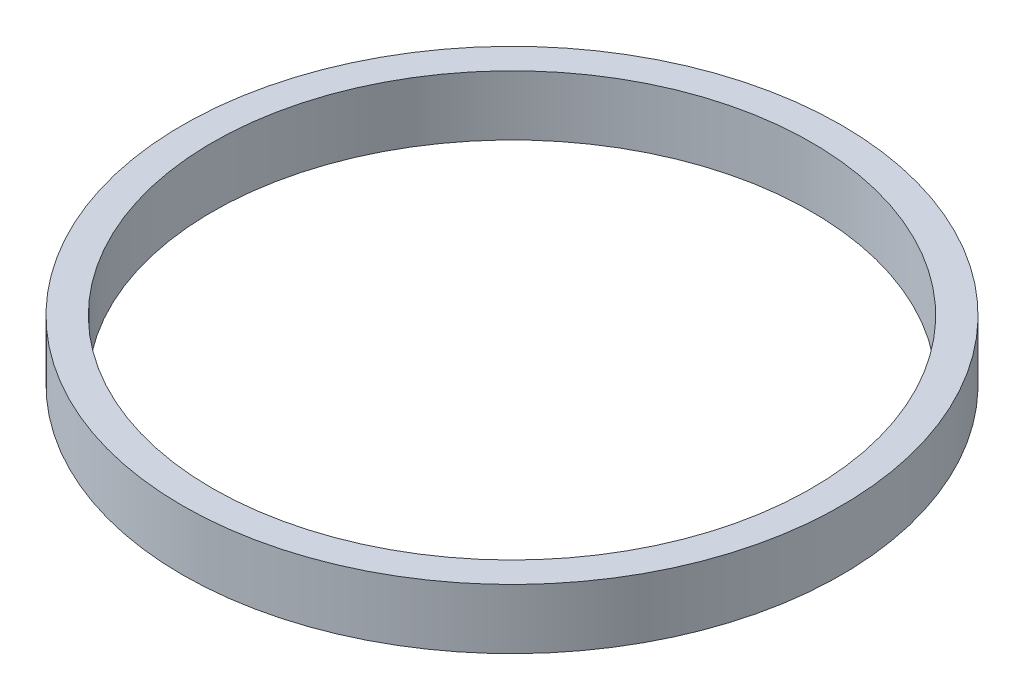
SolidWorks part; units mm, degrees
ref_plane "Спереди" through (0, 0, 0) normal (0, 0, 1) x (1, 0, 0)
ref_plane "Сверху" through (0, 0, 0) normal (0, 1, 0) x (1, 0, 0)
ref_plane "Справа" through (0, 0, 0) normal (1, 0, 0) x (0, 0, -1)
sketch "Эскиз1" plane through (0, 0, 0) normal (0, 1, 0) x (1, 0, 0)
  circle A0 centre (0, 0) radius 15
  circle A1 centre (0, 0) radius 16.5
  dimension "D1" = 30
  dimension "D2" = 33
extrude "Бобышка-Вытянуть1" add sketch "Эскиз1" along normal blind 3
